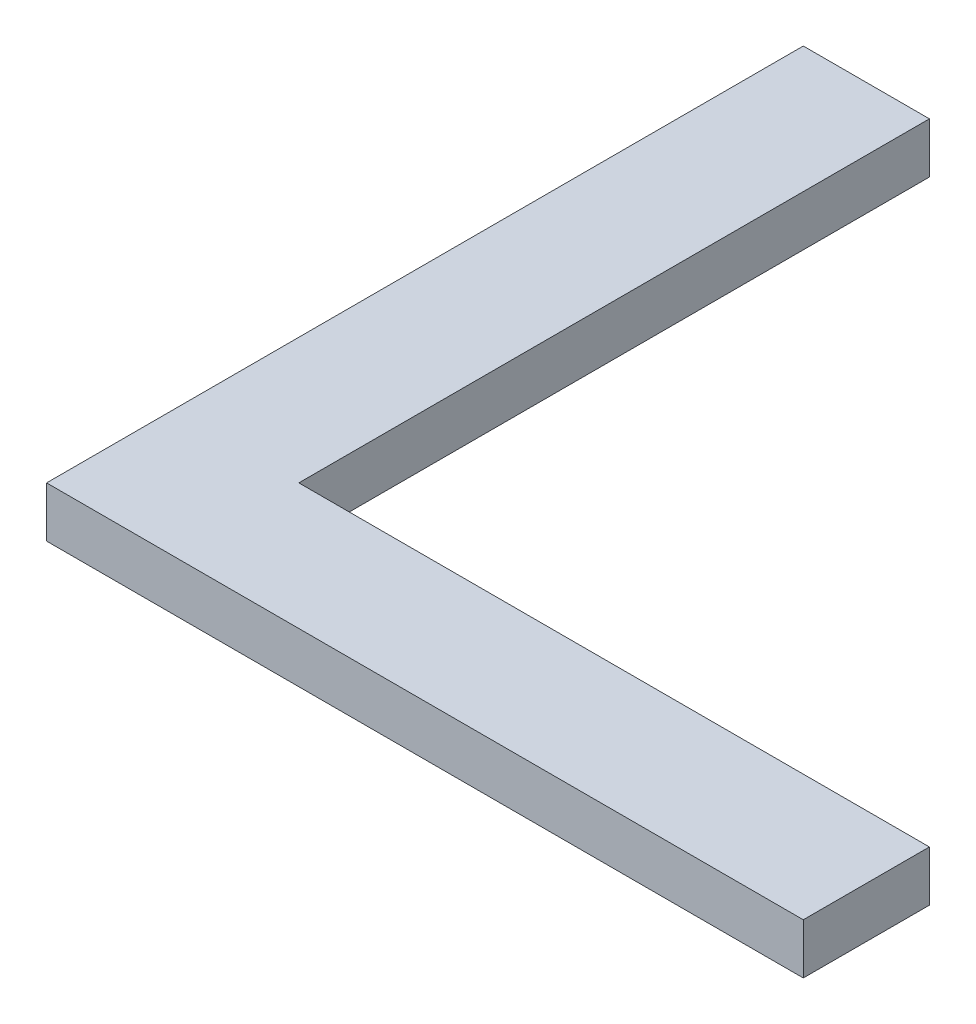
SolidWorks part; units mm, degrees
ref_plane "Front Plane" through (0, 0, 0) normal (0, 0, 1) x (1, 0, 0)
ref_plane "Top Plane" through (0, 0, 0) normal (0, 1, 0) x (1, 0, 0)
ref_plane "Right Plane" through (0, 0, 0) normal (1, 0, 0) x (0, 0, -1)
sketch "Sketch1" plane through (0, 0, 0) normal (0, 1, 0) x (1, 0, 0)
  line L0 (31.75, 0) -> (0, 0)
  line L1 (0, 0) -> (0, 31.75)
  line L2 (0, 31.75) -> (-6.35, 31.75)
  line L3 (-6.35, 31.75) -> (-6.35, -6.35)
  line L4 (-6.35, -6.35) -> (31.75, -6.35)
  line L5 (31.75, -6.35) -> (31.75, 0)
  dimension "D1" = 90
  dimension "D2" = 6.35
  dimension "D3" = 31.75
extrude "Boss-Extrude1" add sketch "Sketch1" along normal blind 2.54
